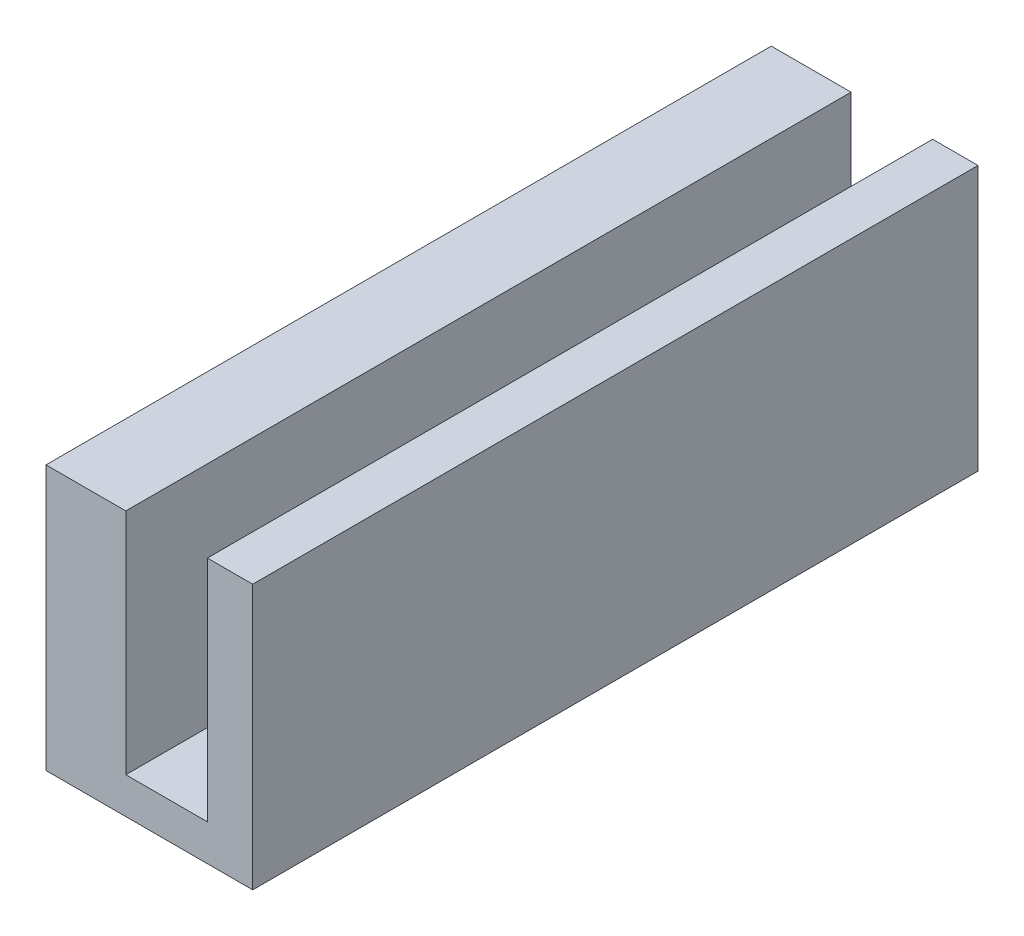
SolidWorks part; units mm, degrees
ref_plane "Front Plane" through (0, 0, 0) normal (0, 0, 1) x (1, 0, 0)
ref_plane "Top Plane" through (0, 0, 0) normal (0, 1, 0) x (1, 0, 0)
ref_plane "Right Plane" through (0, 0, 0) normal (1, 0, 0) x (0, 0, -1)
sketch "Sketch1" plane through (0, 0, 0) normal (0, 1, 0) x (1, 0, 0)
  line L1 (0, 0) -> (5.7, 0)
  line L2 (0, 0) -> (0, 20)
  line L3 (0, 20) -> (5.7, 20)
  line L4 (5.7, 0) -> (5.7, 20)
  dimension "D1" = 5.7
  dimension "D2" = 20
extrude "Boss-Extrude1" add sketch "Sketch1" along normal blind 1
sketch "Sketch2" plane through (0, 1, 0) normal (0, 1, 0) x (1, 0, 0)
  line L0 (0, 0) -> (5.7, 0) construction
  line L1 (0, 20) -> (2.2, 20)
  line L2 (0, 20) -> (0, 0)
  line L3 (0, 0) -> (2.2, 0)
  line L4 (2.2, 20) -> (2.2, 0)
  line L6 (5.7, 20) -> (4.45, 20)
  line L7 (5.7, 20) -> (5.7, 0)
  line L8 (5.7, 0) -> (4.45, 0)
  line L9 (4.45, 20) -> (4.45, 0)
  dimension "D1" = 2.2
  dimension "D2" = 1.25
extrude "Boss-Extrude2" add sketch "Sketch2" along normal blind 6.3
